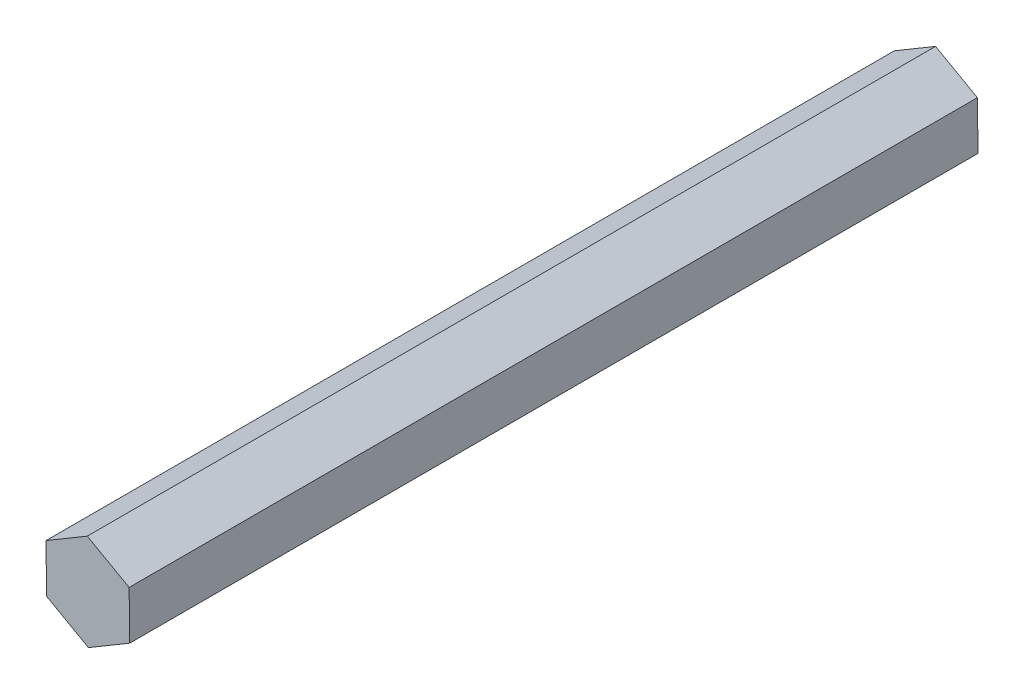
SolidWorks part; units mm, degrees
ref_plane "Front" through (0, 0, 0) normal (0, 0, 1) x (1, 0, 0)
ref_plane "Top" through (0, 0, 0) normal (0, 1, 0) x (1, 0, 0)
ref_plane "Right" through (0, 0, 0) normal (1, 0, 0) x (0, 0, -1)
sketch "Sketch1" plane through (0, 0, 0) normal (0, 0, 1) x (1, 0, 0)
  line L1 (1.2165, 0.7217) -> (-0.0168, 1.4144)
  line L2 (-0.0168, 1.4144) -> (-1.2333, 0.6927)
  line L3 (-1.2333, 0.6927) -> (-1.2165, -0.7217)
  line L4 (-1.2165, -0.7217) -> (0.0168, -1.4144)
  line L5 (0.0168, -1.4144) -> (1.2333, -0.6927)
  line L6 (1.2333, -0.6927) -> (1.2165, 0.7217)
  circle A0 centre (0, 0) radius 1.225 construction
  dimension "D1" = 2.45
extrude "Boss-Extrude1" add sketch "Sketch1" along normal blind 25
